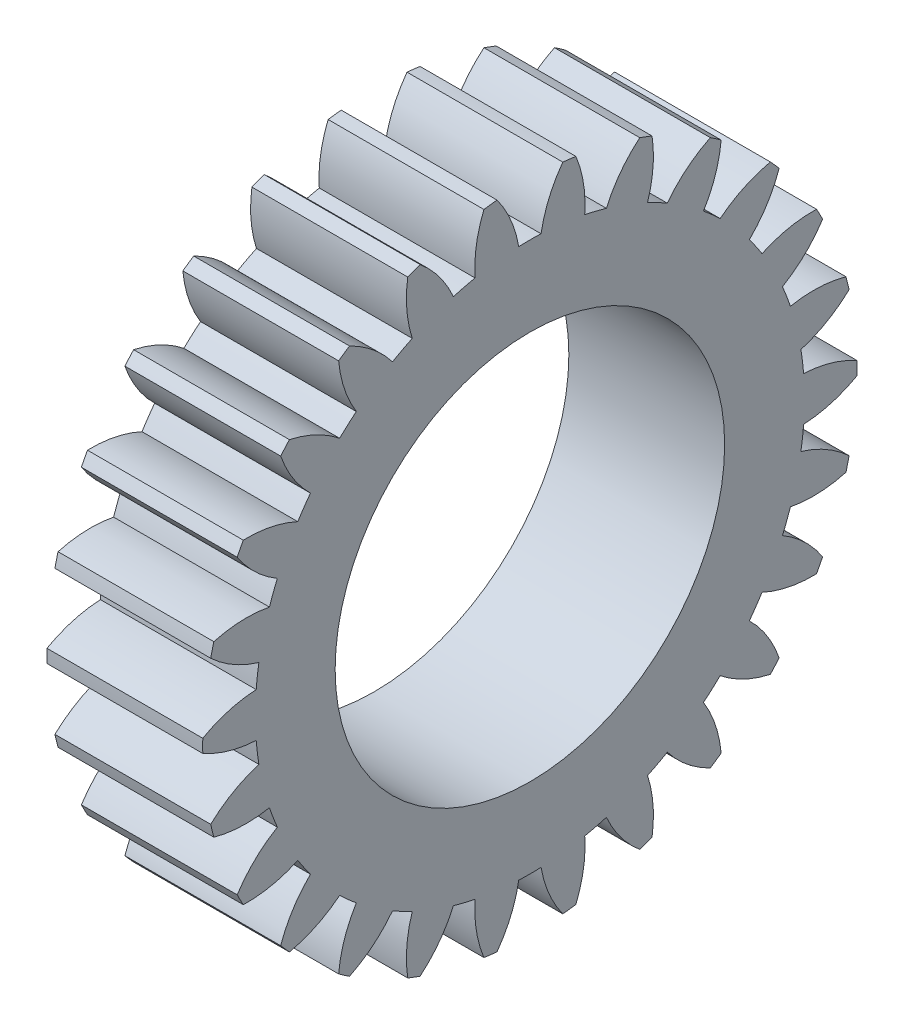
SolidWorks part; units mm, degrees
ref_plane "Plane1" through (0, 0, 0) normal (0, 0, 1) x (1, 0, 0)
ref_plane "Plane2" through (0, 0, 0) normal (0, 1, 0) x (1, 0, 0)
ref_plane "Plane3" through (0, 0, 0) normal (1, 0, 0) x (0, 0, -1)
sketch "HoldingSke" plane through (0, 0, 0) normal (0, 1, 0) x (1, 0, 0)
  line L0 (0, 0) -> (1.498, -0.7306)
  line L1 (-15, 0) -> (100, 0) construction
  line L2 (0, 0) -> (-2.1039, 2.3779)
  line L3 (0, 0) -> (-11.863, 4.5341)
  line L4 (0, 0) -> (7.762, 3.7858)
  line L5 (0, 0) -> (-46.8476, -17.4728)
  line L6 (0, 0) -> (-3.3159, -2.2372)
  line L7 (-2.1039, 2.3779) -> (8.6586, 51.2059)
  line L8 (-76.2, 54.61) -> (-74.4, 54.61)
  line L9 (-71.009, 38.7566) -> (-53.1078, 45.2721)
  line L10 (-76.2, 71.12) -> (104.1128, 71.12)
  line L11 (0, 0) -> (-4, 0)
  line L12 (-76.2, 101.6) -> (-76.177, 101.6)
  line L13 (24.9733, 27.94) -> (52.9518, 28.4284)
  line L14 (24.9733, 27.94) -> (24.9743, 27.94)
  line L15 (24.9733, 27.94) -> (100.4006, 29.5858)
  line L16 (-63.627, -0.6) -> (-12.827, -0.6)
  circle A0 centre (0, 0) radius 5
  circle A1 centre (0, 0) radius 7.049
  circle A2 centre (0, 0) radius 37.5
  circle A3 centre (0, 0) radius 5
  dimension "MHD" = 14.098
  dimension "Hub_dia" = 75
  dimension "Bore" = 10
  dimension "MBD" = 10
  dimension "Num_teeth" = 26
  dimension "Pitch" = 1.6667
  dimension "Overall_len" = 50
  dimension "Show_teeth" = 26
  dimension "Thickness" = 4
  dimension "OAL" = 50.0001
  dimension "T_dim" = 1.8
  dimension "Ap" = 20
  dimension "H" = 19.05
  dimension "Pitch_radius" = 180.3128
  dimension "Width" = 4
  dimension "Backlash" = 0.023
  dimension "Addendum_fac" = 1
  dimension "Dedendum_fac" = 1.25
  dimension "Clearance_fac" = 0.25
  dimension "Dedendum_add" = 0.001
  dimension "Module" = 0.6
sketch "BasProSke" plane through (0, 0, 0) normal (0, 1, 0) x (1, 0, 0)
  line L0 (-10, 0) -> (60, 0) construction
  line L1 (0, 0) -> (0, 8.4)
  line L2 (0, 0) -> (4, 0)
  line L3 (4, 0) -> (4, 8.4)
  line L4 (4, 8.4) -> (0, 8.4)
  dimension "Thickness" = 4
  dimension "Diameter" = 16.8
revolve "Base-Revolve" add sketch "BasProSke" angle 360 about L0
sketch "TooCutSke" plane through (0, 0, 0) normal (1, 0, 0) x (0, 0, -1)
  line L1 (0, 0) -> (0, 107) construction
  line L2 (0, 0) -> (-0.5112, 7.7832) construction
  line L3 (0, 0) -> (-1.8775, 15.4626) construction
  line L4 (-0.5112, 7.7832) -> (-0.9388, 7.7313) construction
  arc A0 (0.2864, 7.0432) -> (-0.2864, 7.0432) centre (0, 0) ccw
  arc A1 (0.8619, 8.3812) -> (-0.8619, 8.3812) centre (0, 0) ccw
  circle A2 centre (0, 0) radius 7.8 construction
  circle A3 centre (0, 0) radius 7.3296 construction
  arc A4 (-0.2864, 7.0432) -> (-0.8619, 8.3812) centre (-3.3611, 6.5135) ccw
  arc A5 (0.8619, 8.3812) -> (0.2864, 7.0432) centre (3.3611, 6.5135) ccw
  dimension "Root_dia" = 14.098
  dimension "Overcut_dia" = 16.8508
  dimension "Pitch_dia" = 15.6
  dimension "Base_dia" = 14.6592
  dimension "Flank_rad" = 3.12
  dimension "Half_ang" = 6.923
  dimension "Half_CT" = 0.4307
extrude "ToothCut" cut sketch "TooCutSke" along normal through all
fillet "Breaks" [suppressed] radius 0.012
fillet "RootFillets" [suppressed] radius 0.151
pattern_circular "TeethCuts" count 26 every 13.846 about axis through (-10, 0, 0) along (1, 0, 0) of "ToothCut", "RootFillets", "Breaks"
sketch "HubNeaOneSke" plane through (0, 0, 0) normal (-1, 0, 0) x (0, 0, 1)
  circle A0 centre (0, 0) radius 7.049
  dimension "Diameter" = 14.098
extrude "HubNearOne" [suppressed] add sketch "HubNeaOneSke" along normal blind 46.0001
sketch "HubNeaBotSke" plane through (0, 0, 0) normal (-1, 0, 0) x (0, 0, 1)
  circle A0 centre (0, 0) radius 7.049
  dimension "Diameter" = 14.098
extrude "HubNearBoth" [suppressed] add sketch "HubNeaBotSke" along normal blind 23
ref_plane "FarPln" through (4, 0, 0) normal (1, 0, 0) x (0, 0, -1)
sketch "HubFarSke" plane through (4, 0, 0) normal (1, 0, 0) x (0, 0, -1)
  circle A0 centre (0, 0) radius 7.049
  dimension "Diameter" = 14.098
extrude "HubFar" [suppressed] add sketch "HubFarSke" along normal blind 23
sketch "BorSke" plane through (0, 0, 0) normal (1, 0, 0) x (0, 0, -1)
  circle A0 centre (0, 0) radius 5
  dimension "Diameter" = 10
extrude "Bore" cut sketch "BorSke" along normal mid plane 100.0001
sketch "KeySke" plane through (0, 0, 0) normal (1, 0, 0) x (0, 0, -1)
  line L0 (-2, 0) -> (-2, 6.8)
  line L1 (-2, 6.8) -> (2, 6.8)
  line L2 (2, 6.8) -> (2, 0)
  line L3 (0, 0) -> (0, 34) construction
  line L4 (-2, 0) -> (2, 0)
  dimension "Width" = 4
  dimension "Offset" = 6.8
extrude "Keyway" [suppressed] cut sketch "KeySke" along normal mid plane 100.0001
pattern_circular "Keyway2" [suppressed] count 2 every 90 about axis through (-10, 0, 0) along (1, 0, 0)
equation "' \"Module@HoldingSke\" = 6.35"
equation "' \"Num_teeth@HoldingSke\" = 12"
equation "' \"Ap@HoldingSke\" =  20"
equation "' \"Ap@HoldingSke\" = 20"
equation "' \"Width@HoldingSke\" = 0.5 * 25.4"
equation "' \"Hub_dia@HoldingSke\"= 1 * 25.4"
equation "' \"Hub_dia@HoldingSke\" = 1 * 25.4"
equation "' \"Overall_len@HoldingSke\" = 1.0 * 25.4"
equation "' \"Bore@HoldingSke\" = 0.75 * 25.4"
equation "' \"T_dim@HoldingSke\" = 0.1 * 25.4"
equation "' \"Width@KeySke\" = 0.25 * 25.4"
equation "' \"Show_teeth@HoldingSke\" = 13"
equation "' \"Backlash@HoldingSke\" = 0.009 * 25.4"
equation "' \"Addendum_fac@HoldingSke\" = 1.0"
equation "' \"Dedendum_fac@HoldingSke\" = 1.25"
equation "' \"Dedendum_add@HoldingSke\" = 0.00005 * 25.4"
equation "' \"Clearance_fac@HoldingSke\" = 0.25"
equation "\"Pitch@HoldingSke\" = 1 / \"Module@HoldingSke\""
equation "\"Overcut_dia@TooCutSke\" = (\"Num_teeth@HoldingSke\" + 2 * \"Addendum_fac@HoldingSke\") / \"Pitch@HoldingSke\" + 0.002 * 25.4"
equation "\"Pitch_dia@TooCutSke\" = \"Num_teeth@HoldingSke\" / \"Pitch@HoldingSke\""
equation "\"Base_dia@TooCutSke\" = \"Num_teeth@HoldingSke\" / \"Pitch@HoldingSke\" * cos((\"Ap@HoldingSke\"  * 3.14159265 / 180))"
equation "\"Root_dia@TooCutSke\" = (\"Num_teeth@HoldingSke\" + 2) / \"Pitch@HoldingSke\" - 2 * (\"Addendum_fac@HoldingSke\" + \"Dedendum_fac@HoldingSke\") / \"Pitch@HoldingSke\" - \"Dedendum_add@HoldingSke\" * 2"
equation "\"Half_ang@TooCutSke\" = 180 / \"Num_teeth@HoldingSke\""
equation "\"Half_CT@TooCutSke\" = \"Num_teeth@HoldingSke\" / \"Pitch@HoldingSke\" * sin((3.14159265 / 2 / \"Num_teeth@HoldingSke\")) / 2 - 7 * \"Backlash@HoldingSke\" / 4"
equation "\"Flank_rad@TooCutSke\" = \"Num_teeth@HoldingSke\" / \"Pitch@HoldingSke\" / 5"
equation "\"Radius@RootFillets\" = \"Clearance_fac@HoldingSke\" / \"Pitch@HoldingSke\" + \"Dedendum_add@HoldingSke\""
equation "\"Break_rad@Breaks\" = 0.02 / \"Pitch@HoldingSke\""
equation "\"Thickness@HoldingSke\" = \"Width@HoldingSke\""
equation "\"OAL@HoldingSke\" = \"Thickness@HoldingSke\""
equation "\"MHD@HoldingSke\" = (\"Num_teeth@HoldingSke\" + 2) / \"Pitch@HoldingSke\" - 2 * (\"Addendum_fac@HoldingSke\" + \"Dedendum_fac@HoldingSke\")  / \"Pitch@HoldingSke\" - \"Dedendum_add@HoldingSke\" * 2"
equation "\"MBD@HoldingSke\" = (\"Num_teeth@HoldingSke\" + 2) / \"Pitch@HoldingSke\" - 2 * (\"Addendum_fac@HoldingSke\" + \"Dedendum_fac@HoldingSke\")  / \"Pitch@HoldingSke\" - \"Dedendum_add@HoldingSke\" * 2 - 0.002 * 25.4"
equation "\"MHD@HoldingSke\" = ((sgn( \"MHD@HoldingSke\" - \"Hub_dia@HoldingSke\" )-1)*( \"MHD@HoldingSke\" - \"Hub_dia@HoldingSke\" ))/-2+ \"Hub_dia@HoldingSke\""
equation "\"MBD@HoldingSke\" = ((sgn( \"MBD@HoldingSke\" - \"Bore@HoldingSke\" )-1)*( \"MBD@HoldingSke\" - \"Bore@HoldingSke\" ))/-2+ \"Bore@HoldingSke\""
equation "\"OAL@HoldingSke\" = ((sgn( \"OAL@HoldingSke\" - \"Overall_len@HoldingSke\" )+1)*( \"OAL@HoldingSke\" - \"Overall_len@HoldingSke\" ))/2 + \"Overall_len@HoldingSke\" + 0.000002 * 25.4"
equation "\"Num_teeth@TeethCuts\" = int( \"Show_teeth@HoldingSke\" ) + 1"
equation "\"Num_teeth@TeethCuts\" = ((sgn( \"Num_teeth@TeethCuts\" - \"Num_teeth@HoldingSke\" )-1)*( \"Num_teeth@TeethCuts\" - \"Num_teeth@HoldingSke\" ))/-2+ \"Num_teeth@HoldingSke\""
equation "\"Num_teeth@TeethCuts\" = ((sgn( \"Num_teeth@TeethCuts\" - 2.0)+1)*( \"Num_teeth@TeethCuts\" - 2.0))/2 +2.0"
equation "\"Angle@TeethCuts\" = 360.0 / \"Num_teeth@HoldingSke\""
equation "\"Diameter@BasProSke\" = (\"Num_teeth@HoldingSke\" + 2 * \"Addendum_fac@HoldingSke\") / \"Pitch@HoldingSke\""
equation "\"Thickness@BasProSke\"  = \"Thickness@HoldingSke\""
equation "' \"Fillet_rad@BasProSke\" =  \"Thickness@HoldingSke\" * 0.05"
equation "' \"Fillet_rad@BasProSke\" = \"Thickness@HoldingSke\" * 0.05"
equation "\"MHD@HoldingSke\" = ((sgn( \"MHD@HoldingSke\" - \"Root_dia@TooCutSke\" )-1)*( \"MHD@HoldingSke\" - \"Root_dia@TooCutSke\" ))/-2+ \"Root_dia@TooCutSke\""
equation "\"Diameter@HubNeaOneSke\" = \"MHD@HoldingSke\""
equation "\"Length@HubNearOne\" = \"OAL@HoldingSke\" - \"Thickness@BasProSke\""
equation "\"Diameter@HubNeaBotSke\" = \"MHD@HoldingSke\""
equation "\"Length@HubNearBoth\" = ( \"OAL@HoldingSke\" - \"Thickness@BasProSke\" ) / 2.0"
equation "\"Thickness@FarPln\" = \"Thickness@BasProSke\""
equation "\"Diameter@HubFarSke\" = \"MHD@HoldingSke\""
equation "\"Length@HubFar\" = ( \"OAL@HoldingSke\" - \"Thickness@BasProSke\" ) / 2.0"
equation "\"Diameter@BorSke\" = \"MBD@HoldingSke\""
equation "\"D1@Bore\" = \"OAL@HoldingSke\" * 2.0"
equation "\"D1@Keyway\" = \"OAL@HoldingSke\" * 2.0"
equation "\"Offset@KeySke\" = \"T_dim@HoldingSke\" + \"MBD@HoldingSke\" / 2.0"
